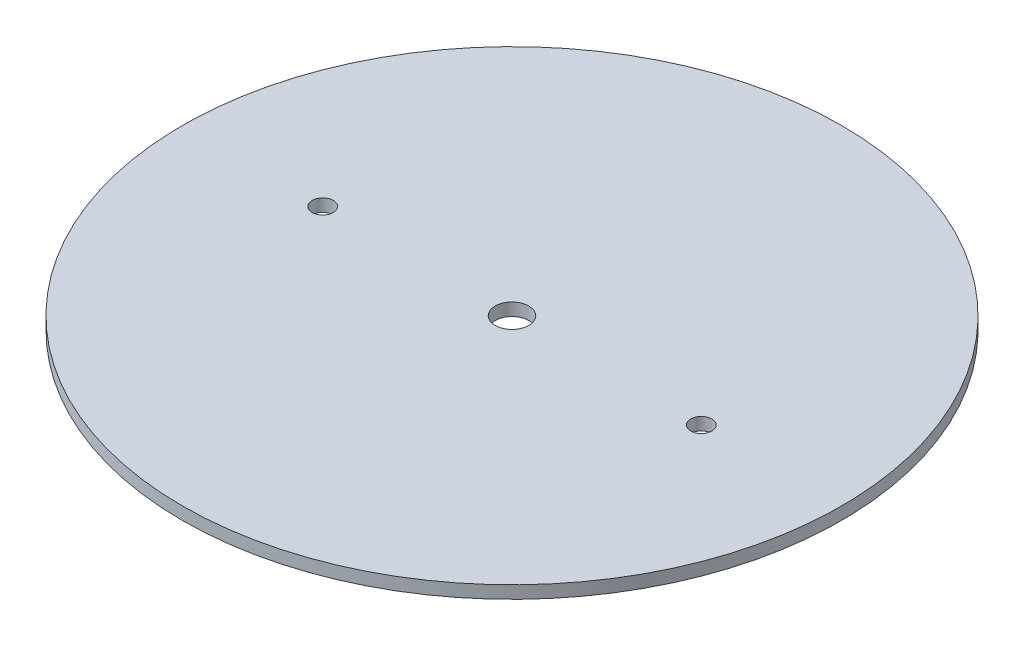
SolidWorks part; units mm, degrees
ref_plane "Front Plane" through (0, 0, 0) normal (0, 0, 1) x (1, 0, 0)
ref_plane "Top Plane" through (0, 0, 0) normal (0, 1, 0) x (1, 0, 0)
ref_plane "Right Plane" through (0, 0, 0) normal (1, 0, 0) x (0, 0, -1)
sketch "Sketch1" plane through (0, 0, 0) normal (0, 1, 0) x (1, 0, 0)
  line L0 (45, 0) -> (-45, 0)
  circle A0 centre (0, 0) radius 78.35
  circle A1 centre (-45, 0) radius 2.5
  circle A2 centre (45, 0) radius 2.5
  circle A3 centre (0, 0) radius 4
  point P6 (0, 0)
  dimension "D1" = 156.7
  dimension "D2" = 5
  dimension "D3" = 5
  dimension "D5" = 8
  dimension "D4" = 90
extrude "Boss-Extrude1" add sketch "Sketch1" along normal blind 3
